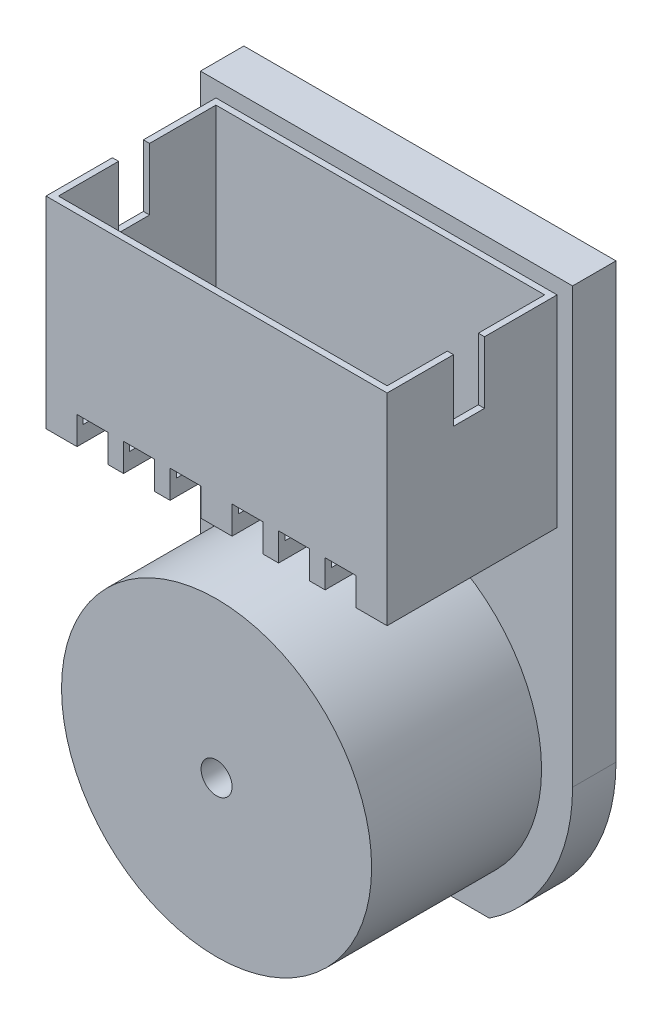
SolidWorks part; units mm, degrees
ref_plane "Front Plane" through (0, 0, 0) normal (0, 0, 1) x (1, 0, 0)
ref_plane "Top Plane" through (0, 0, 0) normal (0, 1, 0) x (1, 0, 0)
ref_plane "Right Plane" through (0, 0, 0) normal (1, 0, 0) x (0, 0, -1)
sketch "Sketch1" plane through (0, 0, 0) normal (0, 0, 1) x (1, 0, 0)
  line L0 (0, 0) -> (0, 50000) construction
  line L1 (0, 0) -> (50000, 0) construction
  line L3 (3.3166, -5) -> (-3.3166, -5)
  line L4 (-6, 0) -> (-6, 14)
  line L5 (6, 14) -> (-6, 14)
  line L6 (6, 0) -> (6, 14)
  arc A0 (3.3166, -5) -> (6, 0) centre (0, 0) ccw
  arc A1 (-6, 0) -> (-3.3166, -5) centre (0, 0) ccw
  dimension "D1" = 12
extrude "Boss-Extrude2" add sketch "Sketch1" along normal blind 1.4 contours L4 L5 L6 A0 L3 A1
ref_plane "Plane2" through (0, 0, 1.4) normal (0, 0, 1) x (1, 0, 0)
sketch "Sketch3" plane through (0, 0, 1.4) normal (0, 0, 1) x (1, 0, 0)
  line L2 (5.5, 7) -> (-5.5, 7)
  line L3 (-5.5, 7) -> (-5.5, 13.5)
  line L4 (5.5, 7) -> (5.5, 13.5)
  line L6 (5.5, 13.5) -> (-5.5, 13.5)
extrude "Boss-Extrude4" add sketch "Sketch3" along normal blind 5.48
sketch "Sketch4" plane through (0, 13.5, 0) normal (0, 1, 0) x (1, 0, 0)
  line L12 (5.3, -1.6) -> (-5.3, -1.6)
  line L13 (-5.3, -1.6) -> (-5.3, -6.68)
  line L14 (-5.3, -6.68) -> (5.3, -6.68)
  line L15 (5.3, -6.68) -> (5.3, -1.6)
  line L16 (5.3, -1.6) -> (-5.3, -1.6)
  line L17 (-5.3, -1.6) -> (-5.3, -6.68)
  line L18 (-5.3, -6.68) -> (5.3, -6.68)
  line L19 (5.3, -6.68) -> (5.3, -1.6)
  dimension "D1" = 0.2
extrude "Cut-Extrude1" cut sketch "Sketch4" against normal blind 5.98
ref_plane "Plane3" through (5.5, 0, 0) normal (1, 0, 0) x (0, 0, -1)
sketch "Sketch6" plane through (5.5, 0, 0) normal (1, 0, 0) x (0, 0, -1)
  line L1 (-6.88, 13.5) -> (-1.4, 13.5) construction
  line L2 (-3.74, 11.5) -> (-4.74, 11.5)
  line L3 (-4.74, 11.5) -> (-4.74, 13.5)
  line L4 (-3.74, 11.5) -> (-3.74, 13.5)
  line L5 (-4.74, 13.5) -> (-3.74, 13.5)
extrude "Cut-Extrude2" cut sketch "Sketch6" against normal blind 11.98
ref_plane "Plane4" through (0, 0, 6.88) normal (0, 0, 1) x (1, 0, 0)
sketch "Sketch7" plane through (0, 0, 6.88) normal (0, 0, 1) x (1, 0, 0)
  line L1 (2, 7) -> (3, 7)
  line L2 (0, 7) -> (0, 50007) construction
  line L3 (0, 7) -> (0, 8)
  line L4 (0.5, 7) -> (0.5, 7.9)
  line L5 (-0.5, 7) -> (-0.5, 7.9)
  line L6 (-0.5, 7.9) -> (-1.5, 7.9)
  line L7 (-1.5, 7.9) -> (-1.5, 7)
  line L8 (0.5, 7) -> (1.5, 7)
  line L9 (-2, 7) -> (-2, 7.9)
  line L10 (-2, 7.9) -> (-3, 7.9)
  line L11 (-3, 7.9) -> (-3, 7)
  line L12 (-1.5, 7) -> (-0.5, 7)
  line L13 (-3.5, 7) -> (-3.5, 7.9)
  line L14 (-3.5, 7.9) -> (-4.5, 7.9)
  line L15 (-4.5, 7.9) -> (-4.5, 7)
  line L16 (-4.5, 7) -> (-3.5, 7)
  line L17 (-3, 7) -> (-2, 7)
  line L18 (0.5, 7.9) -> (1.5, 7.9)
  line L19 (1.5, 7.9) -> (1.5, 7)
  line L20 (2, 7) -> (2, 7.9)
  line L21 (2, 7.9) -> (3, 7.9)
  line L22 (3, 7.9) -> (3, 7)
  line L23 (3.5, 7) -> (3.5, 7.9)
  line L24 (3.5, 7.9) -> (4.5, 7.9)
  line L25 (4.5, 7.9) -> (4.5, 7)
  line L26 (3.5, 7) -> (4.5, 7)
extrude "Cut-Extrude3" cut sketch "Sketch7" against normal blind 1 contours L15 L16 L13 L14 | L11 L17 L9 L10 | L7 L12 L5 L6 | L4 L18 L19 L8 | L20 L21 L22 L1 | L23 L24 L25 L26
ref_plane "Plane5" through (0, 0, 1.4) normal (0, 0, 1) x (1, 0, 0)
sketch "Sketch8" plane through (0, 0, 1.4) normal (0, 0, 1) x (1, 0, 0)
  circle A0 centre (0, 0) radius 5
extrude "Boss-Extrude5" add sketch "Sketch8" along normal blind 5.48
sketch "Sketch9" plane through (0, 0, 6.88) normal (0, 0, 1) x (1, 0, 0)
  circle A0 centre (0, 0) radius 0.5
extrude "Cut-Extrude4" cut sketch "Sketch9" against normal blind 5.48
sketch "Sketch10" plane through (0, 0, 0) normal (0, 0, -1) x (-1, 0, 0)
  circle A0 centre (0, 0) radius 1
extrude "Boss-Extrude6" add sketch "Sketch10" along normal blind 1 contours A0
